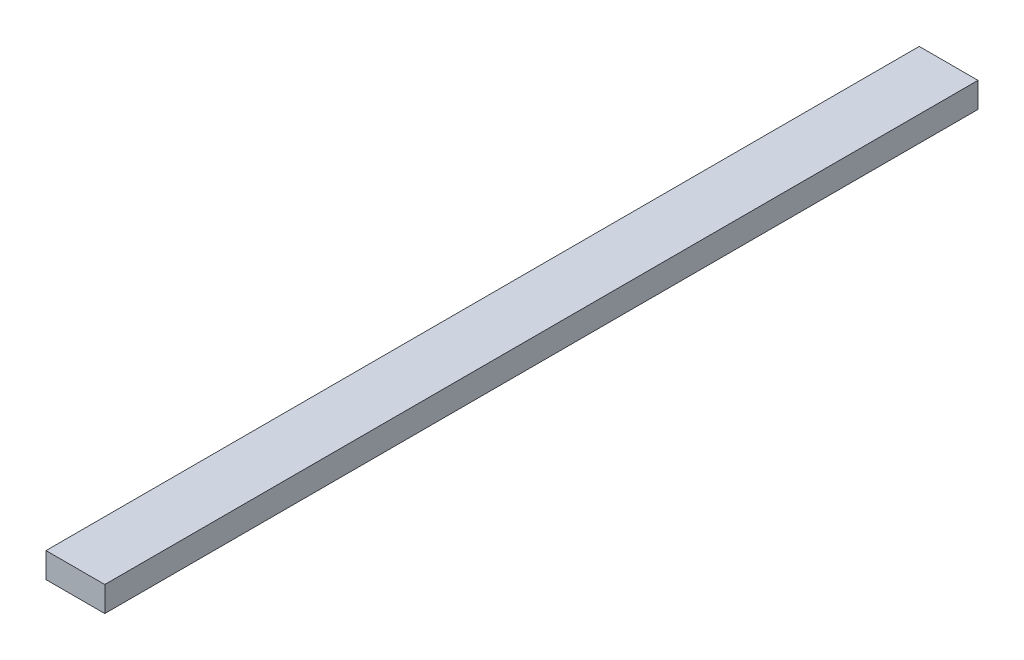
SolidWorks part; units mm, degrees
ref_plane "Front Plane" through (0, 0, 0) normal (0, 0, 1) x (1, 0, 0)
ref_plane "Top Plane" through (0, 0, 0) normal (0, 1, 0) x (1, 0, 0)
ref_plane "Right Plane" through (0, 0, 0) normal (1, 0, 0) x (0, 0, -1)
sketch "Sketch1" plane through (0, 0, 0) normal (0, 0, 1) x (1, 0, 0)
  line L1 (44.45, 19.05) -> (-44.45, 19.05)
  line L2 (44.45, 19.05) -> (44.45, -19.05)
  line L3 (44.45, -19.05) -> (-44.45, -19.05)
  line L4 (-44.45, 19.05) -> (-44.45, -19.05)
  line L5 (44.45, 19.05) -> (-44.45, -19.05) construction
  line L6 (44.45, -19.05) -> (-44.45, 19.05) construction
  point P0 (0, 0)
  dimension "D1" = 88.9
  dimension "D2" = 38.1
extrude "Boss-Extrude1" add sketch "Sketch1" along normal mid plane 1320.8
